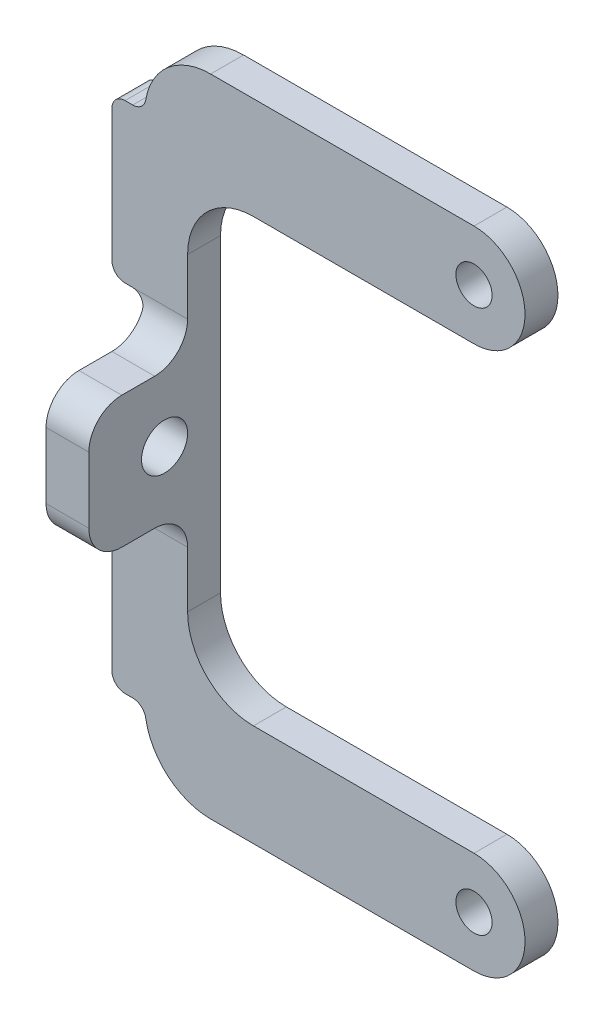
SolidWorks part; units mm, degrees
ref_plane "Front Plane" through (0, 0, 0) normal (0, 0, 1) x (1, 0, 0)
ref_plane "Top Plane" through (0, 0, 0) normal (0, 1, 0) x (1, 0, 0)
ref_plane "Right Plane" through (0, 0, 0) normal (1, 0, 0) x (0, 0, -1)
sketch "Sketch1" plane through (0, 0, 0) normal (0, 0, 1) x (1, 0, 0)
  line L0 (-10, 49) -> (-60, 49)
  line L1 (-10, -49) -> (-60, -49)
  line L2 (-10, -33.5) -> (-60, -33.5)
  line L3 (-10, 33.5) -> (-60, 33.5)
  line L4 (-60, 49) -> (-60, 33.5)
  line L5 (-60, -33.5) -> (-60, -49)
  circle A0 centre (-10, 41.25) radius 2.75 construction
  circle A1 centre (-10, -41.25) radius 2.75 construction
  circle A2 centre (-10, 41.25) radius 2.75
  circle A3 centre (-10, -41.25) radius 2.75
  circle A4 centre (-10, 41.25) radius 7.75
  circle A5 centre (-10, -41.25) radius 7.75
  dimension "D2" = 50
  dimension "D1" = 5
extrude "Boss-Extrude1" add sketch "Sketch1" along normal blind 5 contours A4 L0 L4 L3 | A4 A2 | A5 A3 | A5 L2 L5 L1
sketch "Sketch2" plane through (0, 0, 5) normal (0, 0, 1) x (1, 0, 0)
  line L0 (-46, 7.5) -> (-46, -7.5)
  line L1 (-53.5, 7.5) -> (-53.5, -7.5)
  line L2 (-60, 33.5) -> (-60, -33.5)
  line L3 (-60, -33.5) -> (-53.5, -33.5)
  line L4 (-10, -33.5) -> (-60, -33.5) construction
  line L5 (-53.5, -33.5) -> (-53.5, 33.5)
  line L6 (-10, 33.5) -> (-60, 33.5) construction
  line L7 (-53.5, 33.5) -> (-60, 33.5)
  line M4 (-10, -33.5) -> (-60, -33.5)
  dimension "D1" = 7.5
extrude "Boss-Extrude2" add sketch "Sketch2" against normal up to surface (5 mm away) contours L5 L7 L2 L1 M4 up to face at (-33.0625, 41.25, 0)
sketch "Sketch3" plane through (0, 0, 5) normal (0, 0, 1) x (1, 0, 0)
  line L0 (-53.5, 0) -> (-60, 0)
  line L1 (-53.5, -33.5) -> (-53.5, 33.5) construction
  line L2 (-60, 49) -> (-60, -49) construction
  line L3 (-53.5, 10) -> (-60, 10)
  line L4 (-53.5, -10) -> (-60, -10)
  line L6 (-60, 10) -> (-53.5, 10)
  line L7 (-60, 10) -> (-60, -10)
  line L8 (-60, -10) -> (-53.5, -10)
  line L9 (-53.5, 10) -> (-53.5, -10)
  line M6 (-60, 49) -> (-60, -49)
  line M10 (-53.5, -33.5) -> (-53.5, 33.5)
  dimension "D1" = 10
  dimension "D2" = 10
extrude "Boss-Extrude3" add sketch "Sketch3" along normal blind 10 contours L3 L0 M10 M6 | L4 L0 M10 M6
sketch "Sketch4" plane through (0, 0, 15) normal (0, 0, 1) x (1, 0, 0)
  line L4 (-53.5, -10) -> (-53.5, 10)
  line L5 (-53.5, 10) -> (-60, 10)
  line L6 (-60, 10) -> (-60, -10)
  line L7 (-60, -10) -> (-53.5, -10)
  line L8 (-53.5, -10) -> (-53.5, 10)
  line L9 (-53.5, 10) -> (-60, 10)
  line L10 (-60, 10) -> (-60, -10)
  line L11 (-60, -10) -> (-53.5, -10)
  dimension "D1" = 0
extrude "Boss-Extrude4" add sketch "Sketch4" along normal blind 5
fillet "Fillet1" radius 5 4 edges at (-56.75, 10, 5) (-56.75, 10, 20) (-56.75, -10, 20) (-56.75, -10, 5)
sketch "Sketch6" plane through (-53.5, 0, 0) normal (1, 0, 0) x (0, 0, -1)
  circle A0 centre (-8.5, 0) radius 3.5
  dimension "D1" = 7
extrude "Cut-Extrude1" cut sketch "Sketch6" against normal blind 5
sketch "Sketch7" plane through (-60, 0, 0) normal (-1, 0, 0) x (0, 0, 1)
  line L0 (8.5, 0) -> (8.5, -9)
  line L1 (8.5, 0) -> (8.5, 9)
  line L2 (10, 0) -> (10, -9)
  line L3 (10, 0) -> (10, 9)
  line L4 (7, 0) -> (7, -9)
  line L5 (7, 0) -> (7, 9)
  line L6 (10, 9) -> (7, 9)
  line L7 (7, -9) -> (10, -9)
  dimension "D2" = 9
  dimension "D1" = 9
  dimension "D3" = 1.5
  dimension "D4" = 1.5
extrude "Cut-Extrude2" cut sketch "Sketch7" against normal blind 3
sketch "Sketch9" plane through (-57, 0, 0) normal (-1, 0, 0) x (0, 0, 1)
  line L3 (7, -3.1623) -> (7, -9)
  line L4 (7, -9) -> (10, -9)
  line L5 (10, -9) -> (10, -3.1623)
  line L6 (7, -3.1623) -> (7, -9)
  line L7 (7, -9) -> (10, -9)
  line L8 (10, -9) -> (10, -3.1623)
  arc A1 (7, -3.1623) -> (10, -3.1623) centre (8.5, 0) ccw
  arc A2 (7, -3.1623) -> (10, -3.1623) centre (8.5, 0) ccw
  dimension "D1" = 0
extrude "Boss-Extrude5" add sketch "Sketch9" along normal blind 3
fillet "Fillet2" radius 10 4 edges at (-53.5, 33.5, 2.5) (-53.5, -33.5, 2.5) (-60, -49, 2.5) (-60, 49, 2.5)
sketch "Sketch10" plane through (-60, 0, 0) normal (-1, 0, 0) x (0, 0, 1)
  line L0 (5, 15) -> (0, 15)
  line L1 (5, -15) -> (0, -15)
  line L8 (0, 39) -> (0, -39)
  line L9 (0, -39) -> (5, -39)
  line L10 (5, -39) -> (5, -15)
  line L11 (10, -10) -> (15, -10)
  line L12 (20, -5) -> (20, 5)
  line L13 (15, 10) -> (10, 10)
  line L14 (5, 15) -> (5, 39)
  line L15 (5, 39) -> (0, 39)
  line L16 (0, 39) -> (0, -39)
  line L17 (0, -39) -> (5, -39)
  line L18 (5, -39) -> (5, -15)
  line L19 (10, -10) -> (15, -10)
  line L20 (20, -5) -> (20, 5)
  line L21 (15, 10) -> (10, 10)
  line L22 (5, 15) -> (5, 39)
  line L23 (5, 39) -> (0, 39)
  arc A4 (10, -10) -> (5, -15) centre (10, -15) ccw
  arc A5 (15, -10) -> (20, -5) centre (15, -5) ccw
  arc A6 (20, 5) -> (15, 10) centre (15, 5) ccw
  arc A7 (5, 15) -> (10, 10) centre (10, 15) ccw
  arc A8 (10, -10) -> (5, -15) centre (10, -15) ccw
  arc A9 (15, -10) -> (20, -5) centre (15, -5) ccw
  arc A10 (20, 5) -> (15, 10) centre (15, 5) ccw
  arc A11 (5, 15) -> (10, 10) centre (10, 15) ccw
  line M17 (0, 39) -> (0, -39)
  line M18 (0, -39) -> (5, -39)
  line M19 (5, -39) -> (5, -15)
  line M27 (5, 15) -> (5, 39)
  line M28 (5, 39) -> (0, 39)
  dimension "D1" = 0
extrude "Boss-Extrude6" add sketch "Sketch10" along normal blind 5 contours L1 M19 M17 M18 | L0 M27 M28 M17
fillet "Fillet3" radius 2 8 edges at (-60, -39, 2.5) (-65, -39, 2.5) (-65, -15, 2.5) (-60, -15, 2.5) (-60, 15, 2.5) (-65, 15, 2.5) (-65, 39, 2.5) (-60, 39, 2.5)
